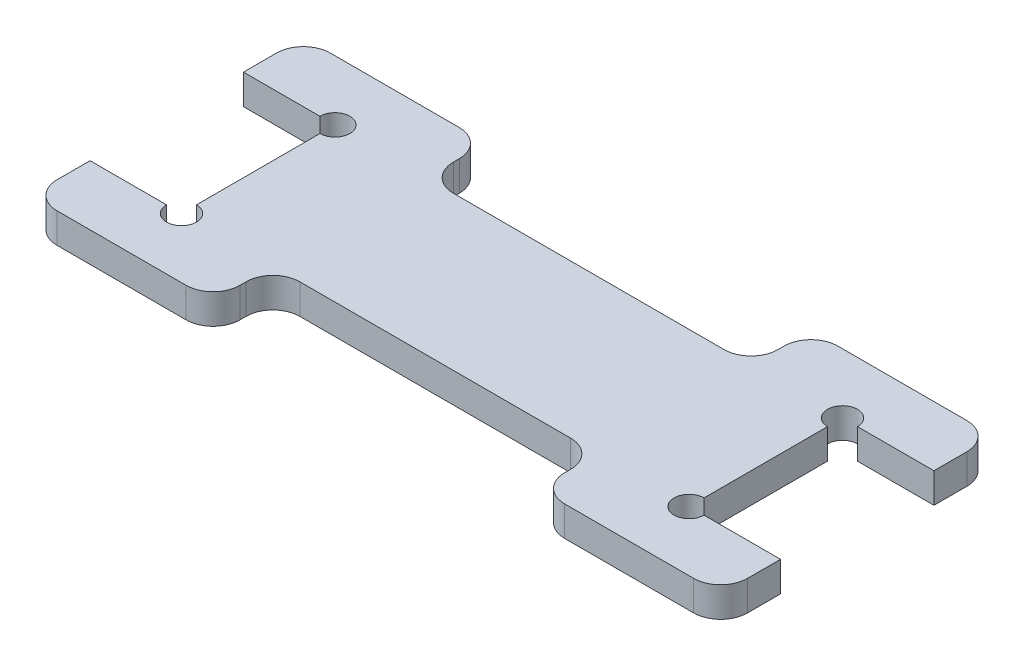
SolidWorks part; units mm, degrees
ref_plane "Front Plane" through (0, 0, 0) normal (0, 0, 1) x (1, 0, 0)
ref_plane "Top Plane" through (0, 0, 0) normal (0, 1, 0) x (1, 0, 0)
ref_plane "Right Plane" through (0, 0, 0) normal (1, 0, 0) x (0, 0, -1)
sketch "Sketch1" plane through (0, 0, 0) normal (0, 1, 0) x (1, 0, 0)
  line L0 (-57.61, -12.8) -> (-42.35, -12.8)
  line L5 (42.35, -12.8) -> (-42.35, -12.8)
  line L6 (42.35, -12.8) -> (42.35, 12.8)
  line L11 (42.35, 12.8) -> (-42.35, 12.8)
  line L12 (-42.35, -12.8) -> (-42.35, 12.8)
  line L13 (0, 12.8) -> (0, -12.8) construction
  line L14 (42.35, 0) -> (-42.35, 0) construction
  line L15 (-57.61, 22.8) -> (-27.09, 22.8)
  line L16 (-57.61, 22.8) -> (-57.61, 12.8)
  line L17 (-57.61, 12.8) -> (-42.35, 12.8)
  line L18 (-27.09, 22.8) -> (-27.09, 12.8)
  line L19 (-42.35, 12.8) -> (-42.35, 22.8) construction
  line L20 (-57.61, 17.8) -> (-27.09, 17.8) construction
  line L21 (-57.61, -22.8) -> (-57.61, -12.8)
  line L22 (-57.61, -22.8) -> (-27.09, -22.8)
  line L23 (-27.09, -22.8) -> (-27.09, -12.8)
  line L24 (57.61, -12.8) -> (42.35, -12.8)
  line L25 (27.09, -22.8) -> (27.09, -12.8)
  line L26 (57.61, -22.8) -> (27.09, -22.8)
  line L27 (57.61, -22.8) -> (57.61, -12.8)
  line L28 (27.09, 22.8) -> (27.09, 12.8)
  line L29 (57.61, 12.8) -> (42.35, 12.8)
  line L30 (57.61, 22.8) -> (57.61, 12.8)
  line L31 (57.61, 22.8) -> (27.09, 22.8)
  arc A0 (-42.35, 10.3) -> (-44.85, 12.8) centre (-42.35, 12.8) ccw
  arc A1 (-42.35, -10.3) -> (-44.85, -12.8) centre (-42.35, -12.8) cw
  arc A2 (42.35, -10.3) -> (44.85, -12.8) centre (42.35, -12.8) ccw
  arc A3 (42.35, 10.3) -> (44.85, 12.8) centre (42.35, 12.8) cw
  point P0 (0, 0)
  point P125 (-42.35, 17.8)
  dimension "D5" = 5
  dimension "D1" = 25.6
  dimension "D2" = 84.7
  dimension "D3" = 15.26
  dimension "D4" = 10
extrude "Boss-Extrude1" add sketch "Sketch1" along normal blind 5 contours A0 L11 L18 L15 L16 L17 | L6 A3 L11 A0 L12 A1 L5 A2 | L5 A1 L0 L21 L22 L23 | A2 L5 L25 L26 L27 L24 | L11 A3 L29 L30 L31 L28
fillet "Fillet1" radius 4.5 12 edges at (27.09, 2.5, 12.8) (27.09, 2.5, -12.8) (-27.09, 2.5, 12.8) (-27.09, 2.5, -12.8) (-57.61, 2.5, -22.8) (27.09, 2.5, -22.8) (57.61, 2.5, -22.8) (57.61, 2.5, 22.8) (27.09, 2.5, 22.8) (-57.61, 2.5, 22.8) (-27.09, 2.5, 22.8) (-27.09, 2.5, -22.8)
